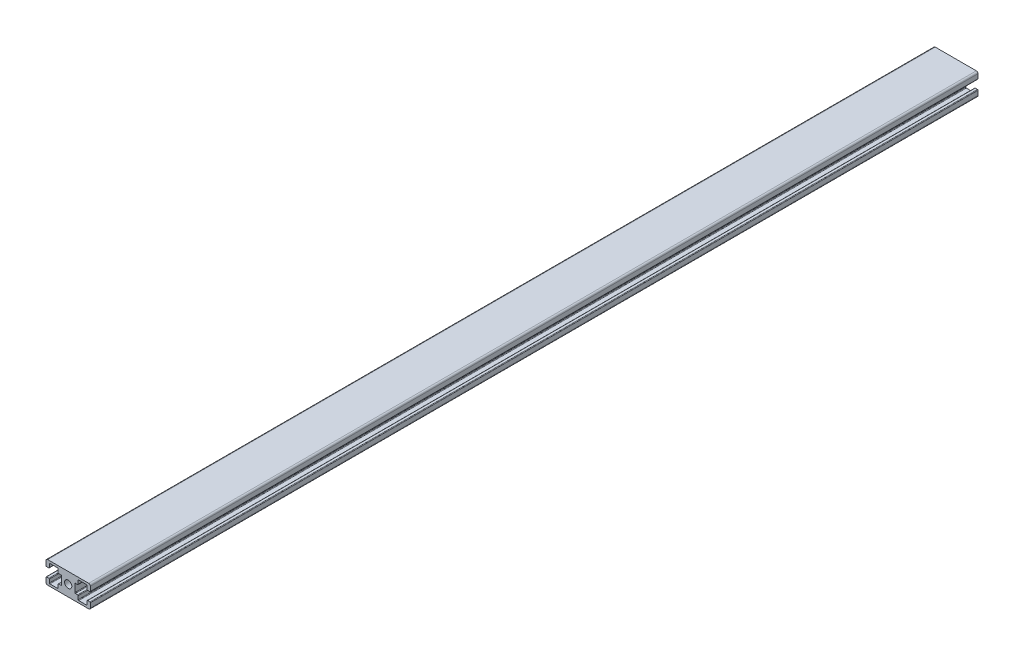
SolidWorks part; units mm, degrees
material "6063-T5"
ref_plane "Front Plane" through (0, 0, 0) normal (0, 0, 1) x (1, 0, 0)
ref_plane "Top Plane" through (0, 0, 0) normal (0, 1, 0) x (1, 0, 0)
ref_plane "Right Plane" through (0, 0, 0) normal (1, 0, 0) x (0, 0, -1)
sketch "Sketch1" plane through (0, 0, 0) normal (0, 0, 1) x (1, 0, 0)
  line L0 (1.5, 0) -> (38.5, 0)
  line L1 (40, 1.5) -> (40, 5.5)
  line L2 (38.5, 20) -> (1.5, 20)
  line L3 (0, 18.5) -> (0, 14.5)
  line L4 (0.5, 14) -> (2.5, 14)
  line L5 (0.5, 6) -> (2.5, 6)
  line L6 (39.5, 14) -> (37.5, 14)
  line L7 (39.5, 6) -> (37.5, 6)
  line L8 (40, 14.5) -> (40, 18.5)
  line L9 (0, 5.5) -> (0, 1.5)
  line L10 (37, 14.5) -> (37, 17.5)
  line L11 (37, 5.5) -> (37, 2.5)
  line L12 (3, 14.5) -> (3, 17.5)
  line L13 (3, 5.5) -> (3, 2.5)
  line L14 (3.5, 18) -> (10.5, 18)
  line L15 (11, 17.5) -> (11, 14.5)
  line L16 (26, 13.5) -> (26, 6.5)
  line L17 (14, 13.5) -> (14, 6.5)
  line L18 (11.5, 14) -> (13.5, 14)
  line L19 (3.5, 2) -> (10.5, 2)
  line L20 (11, 2.5) -> (11, 5.5)
  line L21 (11.5, 6) -> (13.5, 6)
  line L22 (36.5, 18) -> (29.5, 18)
  line L23 (29, 17.5) -> (29, 14.5)
  line L24 (28.5, 14) -> (26.5, 14)
  line L25 (36.5, 2) -> (29.5, 2)
  line L26 (29, 2.5) -> (29, 5.5)
  line L27 (28.5, 6) -> (26.5, 6)
  circle A0 centre (20, 10) radius 3.25
  arc A1 (37, 2.5) -> (36.5, 2) centre (36.5, 2.5) cw
  arc A2 (29.5, 2) -> (29, 2.5) centre (29.5, 2.5) cw
  arc A3 (29, 5.5) -> (28.5, 6) centre (28.5, 5.5) ccw
  arc A4 (26, 6.5) -> (26.5, 6) centre (26.5, 6.5) ccw
  arc A5 (26, 13.5) -> (26.5, 14) centre (26.5, 13.5) cw
  arc A6 (29, 14.5) -> (28.5, 14) centre (28.5, 14.5) cw
  arc A7 (37, 17.5) -> (36.5, 18) centre (36.5, 17.5) ccw
  arc A8 (29.5, 18) -> (29, 17.5) centre (29.5, 17.5) ccw
  arc A9 (10.5, 18) -> (11, 17.5) centre (10.5, 17.5) cw
  arc A10 (11, 14.5) -> (11.5, 14) centre (11.5, 14.5) ccw
  arc A11 (14, 13.5) -> (13.5, 14) centre (13.5, 13.5) ccw
  arc A12 (14, 6.5) -> (13.5, 6) centre (13.5, 6.5) cw
  arc A13 (11, 5.5) -> (11.5, 6) centre (11.5, 5.5) cw
  arc A14 (10.5, 2) -> (11, 2.5) centre (10.5, 2.5) ccw
  arc A15 (3, 2.5) -> (3.5, 2) centre (3.5, 2.5) ccw
  arc A16 (3, 17.5) -> (3.5, 18) centre (3.5, 17.5) cw
  arc A17 (38.5, 0) -> (40, 1.5) centre (38.5, 1.5) ccw
  arc A18 (40, 18.5) -> (38.5, 20) centre (38.5, 18.5) ccw
  arc A19 (1.5, 0) -> (0, 1.5) centre (1.5, 1.5) cw
  arc A20 (1.5, 20) -> (0, 18.5) centre (1.5, 18.5) ccw
  arc A21 (37.5, 6) -> (37, 5.5) centre (37.5, 5.5) ccw
  arc A22 (40, 5.5) -> (39.5, 6) centre (39.5, 5.5) ccw
  arc A23 (37.5, 14) -> (37, 14.5) centre (37.5, 14.5) cw
  arc A24 (40, 14.5) -> (39.5, 14) centre (39.5, 14.5) cw
  arc A25 (0.5, 6) -> (0, 5.5) centre (0.5, 5.5) ccw
  arc A26 (2.5, 6) -> (3, 5.5) centre (2.5, 5.5) cw
  arc A27 (2.5, 14) -> (3, 14.5) centre (2.5, 14.5) ccw
  arc A28 (0.5, 14) -> (0, 14.5) centre (0.5, 14.5) cw
  point P69 (0, 0)
extrude "Boss-Extrude1" add sketch "Sketch1" along normal mid plane 800
